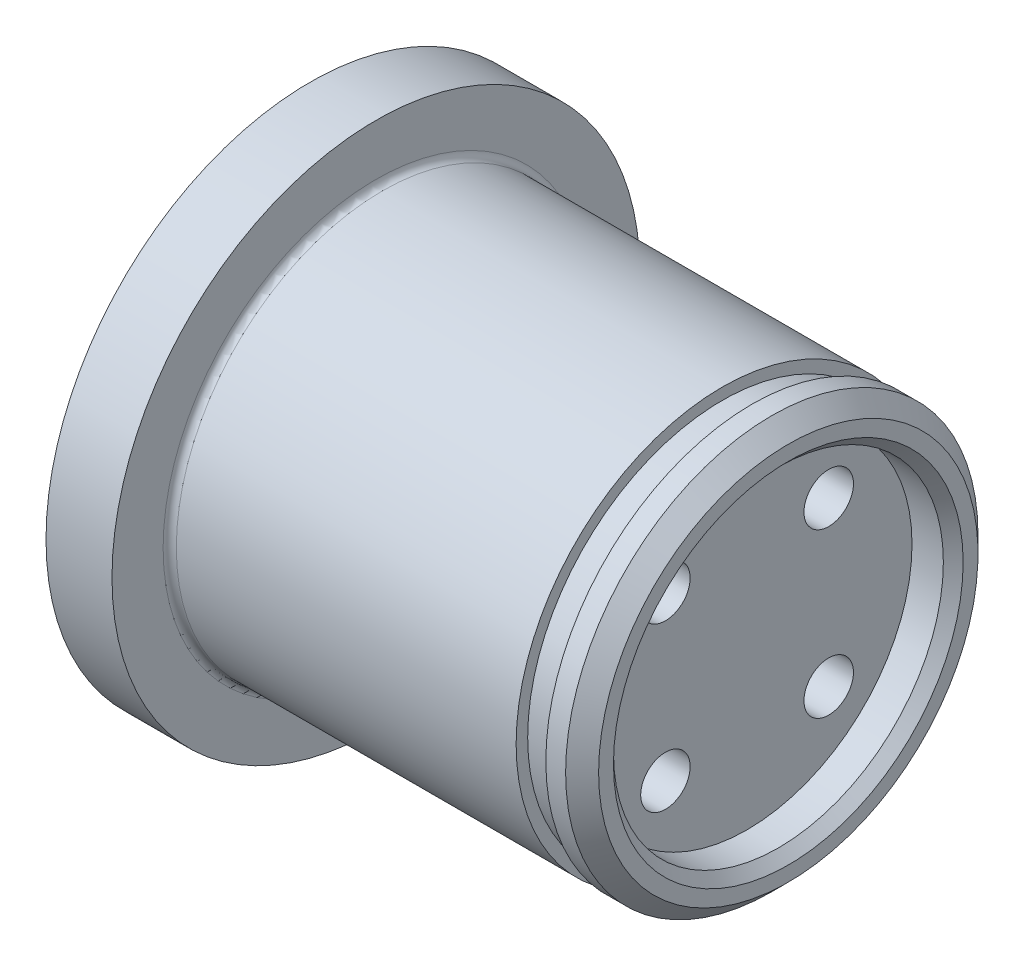
SolidWorks part; units mm, degrees
ref_plane "Спереди" through (0, 0, 0) normal (0, 0, 1) x (1, 0, 0)
ref_plane "Сверху" through (0, 0, 0) normal (0, 1, 0) x (1, 0, 0)
ref_plane "Справа" through (0, 0, 0) normal (1, 0, 0) x (0, 0, -1)
sketch "Эскиз1" plane through (0, 0, 0) normal (0, 0, 1) x (1, 0, 0)
  line L0 (0, 0) -> (22138.4448, 0) construction
  line L1 (0, 0) -> (0, 12.5)
  line L2 (0, 12.5) -> (-25, 12.5)
  line L3 (-25, 12.5) -> (-25, 16)
  line L4 (-25, 16) -> (-29, 16)
  line L5 (-29, 16) -> (-29, 0)
  line L8 (0, 0) -> (-29, 0)
  dimension "D1" = 29
  dimension "D2" = 4
  dimension "D3" = 25
  dimension "D6" = 32
revolve "Повернуть1" add sketch "Эскиз1" angle 360 about L0
sketch "Эскиз2" plane through (0, 0, 0) normal (0, 0, 1) x (1, 0, 0)
  line L0 (-4, 12.5) -> (-4, 11.8)
  line L1 (0, 12.5) -> (-25, 12.5) construction
  line L2 (-4, 11.8) -> (-2.2, 11.8)
  line L3 (-2.2, 11.8) -> (-2.2, 12.5)
  line L4 (-2.2, 12.5) -> (-4, 12.5)
  line L5 (0, -12.5) -> (0, 12.5) construction
  line L6 (0, 0) -> (-50000, 0) construction
  point P10 (-2.2, 12.15)
  point P13 (0, 0)
  dimension "D1" = 4
  dimension "D2" = 1.8
  dimension "D3" = 23.6
revolve "Вырез-Повернуть1" cut sketch "Эскиз2" angle 360 about L6
chamfer "Фаска1" distance 1 angle 45 1 edges at (0, 0, 12.5)
fillet "Скругление1" radius 0.4 1 edges at (-25, 0, 12.5)
hole_wizard "Отверстие1" positions "Эскиз3" profile "Эскиз4" legacy end condition through all
sketch "Эскиз3" plane through (0, 0, 0) normal (1, 0, 0) x (0, 0, -1)
  line L0 (0, 0) -> (0, 7) construction
  line L2 (0, 0) -> (4.9497, 4.9497) construction
  circle A0 centre (0, 0) radius 7 construction
  point P0 (4.9497, 4.9497)
  dimension "D1" = 14
  dimension "D2" = 45
sketch "Эскиз4" plane through (0, 4.9497, -4.9497) normal (0, 1, 0) x (0, 0, -1)
  line L0 (0, 0) -> (0, 29)
  line L1 (0, 29) -> (1.5, 29)
  line L2 (1.5, 29) -> (1.5, 0)
  line L3 (1.5, 0) -> (0, 0)
  line L4 (0, 110) -> (0, -10) construction
  dimension "Диаметр" = 3
  dimension "Глубина" = 29
pattern_circular "Круговой массив1" count 4 over 360 about axis through (0, 0, 0) along (1, 0, 0) of "Отверстие1"
sketch "Эскиз5" plane through (0, 0, 0) normal (0, 0, 1) x (1, 0, 0)
  line L0 (0, 0) -> (0, 10)
  line L1 (0, -11.5) -> (0, 11.5) construction
  line L7 (0, 10) -> (-2.5, 10)
  line L8 (-2.5, 10) -> (-2.5, 0)
  line L9 (-2.5, 0) -> (0, 0)
  line L10 (0, 0) -> (-50000, 0) construction
  dimension "D1" = 2.5
  dimension "D2" = 20
revolve "Вырез-Повернуть2" cut sketch "Эскиз5" angle 360 about L10
chamfer "Фаска2" distance 0.6 angle 45 1 edges at (0, 0, -10)
